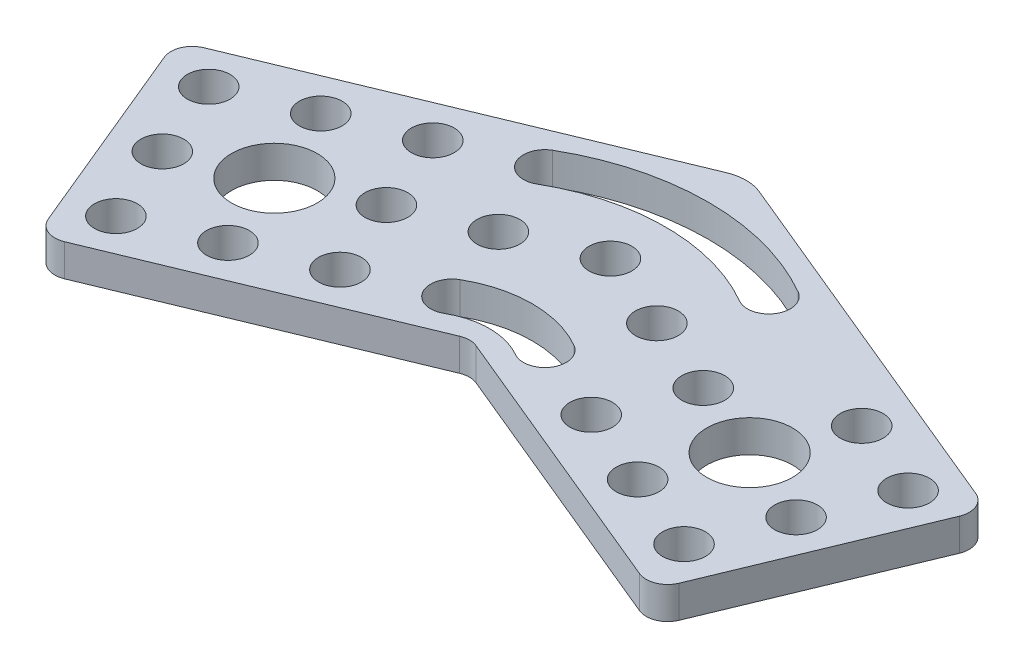
SolidWorks part; units mm, degrees
material "6061 Alloy"
ref_plane "前视基准面" through (0, 0, 0) normal (0, 0, 1) x (1, 0, 0)
ref_plane "上视基准面" through (0, 0, 0) normal (0, 1, 0) x (1, 0, 0)
ref_plane "右视基准面" through (0, 0, 0) normal (1, 0, 0) x (0, 0, -1)
other "Configuration Table"
sketch "Sketch1" plane through (0, 0, 0) normal (0, 1, 0) x (1, 0, 0)
  line L0 (-2, 0) -> (2, 0) construction
  line L1 (0, 0) -> (-33.4302, -13.8473) construction
  line L2 (-7.391, -3.0615) -> (-13.514, 11.7206)
  line L3 (-10.4525, 4.3296) -> (-35.985, -6.2463) construction
  line L4 (-29.5641, -12.2459) -> (-24.4977, -24.4774) construction
  line L5 (0, 0) -> (0, 16.3923)
  line L6 (0, 16.3923) -> (0, -21.2598) construction
  line L7 (-37.0865, -4.5378) -> (-29.4328, -23.0154)
  line L8 (-36.0041, -1.9247) -> (-1.5307, 12.3547)
  line L9 (-26.8197, -24.0978) -> (-0.7654, -13.3057)
  line L10 (26.8197, -24.0978) -> (0.7654, -13.3057)
  line L11 (37.0865, -4.5378) -> (29.4328, -23.0154)
  line L12 (36.0041, -1.9247) -> (1.5307, 12.3547)
  circle A0 centre (0, 0) radius 2
  circle A2 centre (-7.391, -3.0615) radius 2
  circle A3 centre (-14.7821, -6.1229) radius 2
  circle A4 centre (-22.1731, -9.1844) radius 4
  circle A6 centre (-29.5641, -12.2459) radius 2
  circle A8 centre (-10.4525, 4.3296) radius 2
  circle A9 centre (-17.8435, 1.2681) radius 2
  circle A10 centre (-25.2346, -1.7934) radius 2
  circle A11 centre (-32.6256, -4.8548) radius 2
  circle A12 centre (-4.3296, -10.4525) radius 2
  circle A13 centre (-11.7206, -13.514) radius 2
  circle A14 centre (-19.1116, -16.5754) radius 2
  circle A15 centre (-26.5027, -19.6369) radius 2
  circle A16 centre (10.4525, 4.3296) radius 2
  circle A17 centre (7.391, -3.0615) radius 2
  circle A18 centre (14.7821, -6.1229) radius 2
  circle A19 centre (4.3296, -10.4525) radius 2
  circle A20 centre (11.7206, -13.514) radius 2
  circle A21 centre (19.1116, -16.5754) radius 2
  circle A22 centre (26.5027, -19.6369) radius 2
  circle A23 centre (29.5641, -12.2459) radius 2
  circle A24 centre (32.6256, -4.8548) radius 2
  circle A25 centre (25.2346, -1.7934) radius 2
  circle A26 centre (22.1731, -9.1844) radius 4
  arc A27 (-10.4525, 4.3296) -> (10.4525, 4.3296) centre (0, -13.7747) cw construction
  arc A32 (11.4525, 6.0616) -> (-11.4525, 6.0616) centre (0, -13.7747) ccw
  arc A41 (9.4525, 2.5975) -> (-9.4525, 2.5975) centre (0, -13.7747) ccw
  arc A42 (9.4525, 2.5975) -> (11.4525, 6.0616) centre (10.4525, 4.3296) ccw
  arc A43 (-11.4525, 6.0616) -> (-9.4525, 2.5975) centre (-10.4525, 4.3296) ccw
  arc A44 (-4.3296, -10.4525) -> (4.3296, -10.4525) centre (0, -17.9515) cw construction
  arc A45 (5.3296, -8.7205) -> (-5.3296, -8.7205) centre (0, -17.9515) ccw
  arc A46 (3.3296, -12.1846) -> (-3.3296, -12.1846) centre (0, -17.9515) ccw
  arc A47 (3.3296, -12.1846) -> (5.3296, -8.7205) centre (4.3296, -10.4525) ccw
  arc A48 (-5.3296, -8.7205) -> (-3.3296, -12.1846) centre (-4.3296, -10.4525) ccw
  arc A49 (-0.7654, -13.3057) -> (0.7654, -13.3057) centre (0, -15.1535) cw
  arc A50 (37.0865, -4.5378) -> (36.0041, -1.9247) centre (35.2387, -3.7724) ccw
  arc A51 (26.8197, -24.0978) -> (29.4328, -23.0154) centre (27.5851, -22.25) ccw
  arc A52 (-29.4328, -23.0154) -> (-26.8197, -24.0978) centre (-27.5851, -22.25) ccw
  arc A53 (-37.0865, -4.5378) -> (-36.0041, -1.9247) centre (-35.2387, -3.7724) cw
  arc A54 (-1.5307, 12.3547) -> (1.5307, 12.3547) centre (0, 8.6591) cw
  point P60 (0, 7.1303)
  point P66 (0, -9.2924)
  point P77 (0, -12.9887)
  point P80 (37.8519, -2.69)
  point P83 (28.6675, -24.8632)
  point P86 (-28.6675, -24.8632)
  point P89 (-37.8519, -2.69)
  point P92 (0, 12.9887)
  dimension "D1" = 22.5
  dimension "D2" = 8
  dimension "D5" = 8
  dimension "D7" = 8
  dimension "D9" = 8
  dimension "D13" = 4
  dimension "D19" = 2
  dimension "D20" = 4
  dimension "D3" = 8
  dimension "D4" = 8
  dimension "D6" = 90
  dimension "D8" = 90
  dimension "D10" = 8
  dimension "D11" = 8
  dimension "D12" = 90
  dimension "D14" = 4
  dimension "D15" = 4
  dimension "D16" = 4
  dimension "D17" = 4
  dimension "D18" = 4
extrude "Boss-Extrude1" add sketch "Sketch1" along normal blind 3
